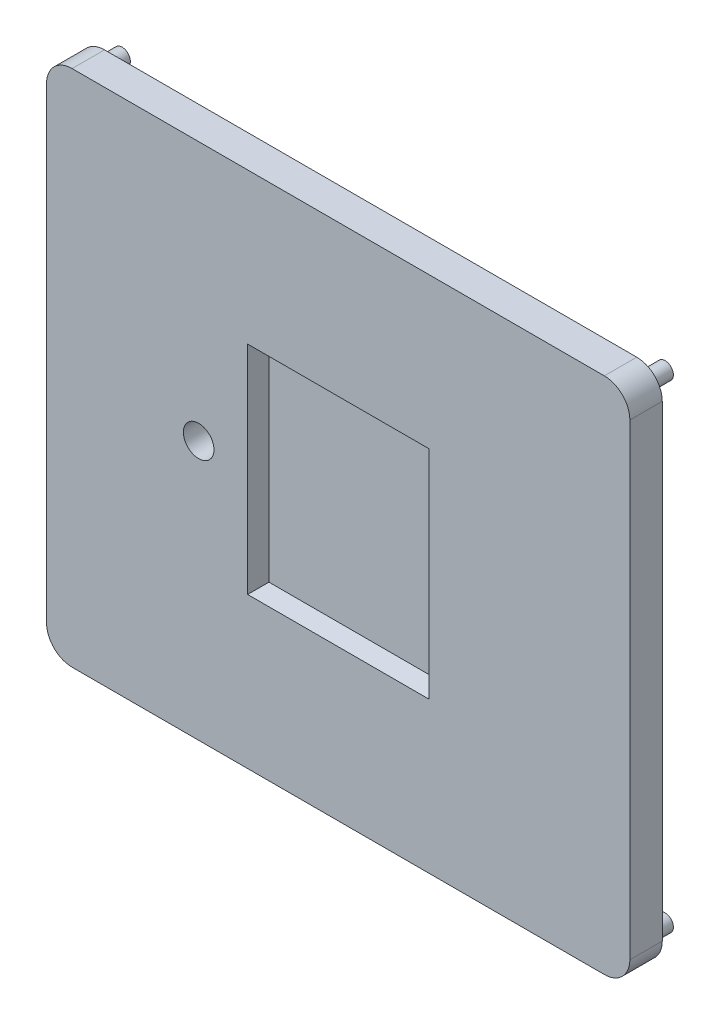
SolidWorks part; units mm, degrees
material "ABS"
ref_plane "Front Plane" through (0, 0, 0) normal (0, 0, 1) x (1, 0, 0)
ref_plane "Top Plane" through (0, 0, 0) normal (0, 1, 0) x (1, 0, 0)
ref_plane "Right Plane" through (0, 0, 0) normal (1, 0, 0) x (0, 0, -1)
sketch "Sketch1" plane through (-2.5661, -10, 0) normal (0, 0, 1) x (1, 0, 0)
  line L1 (-145.6036, 92.4468) -> (62.9964, 92.4468)
  line L2 (-155.6036, 82.4468) -> (-155.6036, -100.7532)
  line L3 (-145.6036, -110.7532) -> (62.9964, -110.7532)
  line L4 (72.9964, 82.4468) -> (72.9964, -100.7532)
  arc A0 (-145.6036, 92.4468) -> (-155.6036, 82.4468) centre (-145.6036, 82.4468) ccw
  arc A1 (-155.6036, -100.7532) -> (-145.6036, -110.7532) centre (-145.6036, -100.7532) ccw
  arc A2 (62.9964, -110.7532) -> (72.9964, -100.7532) centre (62.9964, -100.7532) ccw
  arc A3 (62.9964, 92.4468) -> (72.9964, 82.4468) centre (62.9964, 82.4468) cw
  point P6 (-155.6036, 92.4468)
  point P9 (-155.6036, -110.7532)
  point P14 (72.9964, 92.4468)
  dimension "D3" = 10
  dimension "D4" = 10
  dimension "D5" = 10
  dimension "D6" = 10
  dimension "D1" = 203.2
  dimension "D2" = 228.6
extrude "Lid" add sketch "Sketch1" along normal blind 12.7
sketch "Sketch2" plane through (0, 0, 0) normal (0, 0, 1) x (1, 0, 0)
  line L0 (67.5014, 79.5179) -> (64.8497, 76.8663)
  line L1 (67.5014, -117.8242) -> (64.8497, -115.1726)
  line L2 (-155.2408, 79.5179) -> (-152.5891, 76.8663)
  line L3 (-155.2408, -117.8242) -> (-152.5891, -115.1726)
  line L4 (60.2535, 72.2701) -> (57.7303, 69.7468)
  line L5 (60.2535, -110.5764) -> (68.9341, -119.2569)
  line L6 (-147.9929, -110.5764) -> (-131.8167, -94.4002)
  line L7 (-147.9929, 72.2701) -> (-143.1975, 67.4746)
  line L8 (70.4303, -110.7532) -> (70.4303, 72.4468) construction
  line L9 (57.7303, -108.0532) -> (-145.4697, -108.0532)
  line L10 (57.7303, -108.0532) -> (57.7303, 69.7468)
  line L11 (57.7303, 69.7468) -> (-145.4697, 69.7468)
  line L12 (-145.4697, -108.0532) -> (-145.4697, 69.7468)
  line L13 (-158.1697, 72.4468) -> (-158.1697, -110.7532) construction
  line L14 (60.4303, 82.4468) -> (-148.1697, 82.4468) construction
  arc A0 (70.4303, 72.4468) -> (60.4303, 82.4468) centre (60.4303, 72.4468) ccw construction
  arc A1 (60.4303, -120.7532) -> (70.4303, -110.7532) centre (60.4303, -110.7532) ccw construction
  arc A2 (-148.1697, 82.4468) -> (-158.1697, 72.4468) centre (-148.1697, 72.4468) ccw construction
  arc A3 (-158.1697, -110.7532) -> (-148.1697, -120.7532) centre (-148.1697, -110.7532) ccw construction
  circle A4 centre (62.5516, 74.5682) radius 3.25
  circle A5 centre (62.5516, -112.8745) radius 3.25
  circle A6 centre (-150.291, -112.8745) radius 3.25
  circle A7 centre (-150.291, 74.5682) radius 3.25
  circle A8 centre (62.5516, -112.8745) radius 3.5
  dimension "D1" = 6.5
  dimension "D9" = 7
  dimension "D2" = 7
  dimension "D3" = 7
  dimension "D4" = 7
  dimension "D5" = 7
  dimension "D6" = 12.7
  dimension "D7" = 12.7
  dimension "D8" = 12.7
extrude "Corner Shafts" add sketch "Sketch2" against normal blind 9 contours A4 | A5 | A6 | A7
ref_plane "Top - Outer Plane" through (0, 0, 12.7) normal (0, 0, 1) x (1, 0, 0)
ref_plane "Plane - Top for Kinect" through (0, 0, 12.7) normal (0, 0, 1) x (1, 0, 0)
sketch "Center Lines" plane through (0, 0, 12.7) normal (0, 0, 1) x (1, 0, 0)
  line L0 (70.4303, -19.1532) -> (-185.234, -19.1532) construction
  line L1 (70.4303, -110.7532) -> (70.4303, 72.4468) construction
  line L2 (-43.8697, 82.4468) -> (-43.8697, -133.2416) construction
  line L3 (60.4303, 82.4468) -> (-148.1697, 82.4468) construction
ref_plane "Plane - Base for Kinect" through (0, 0, 6.35) normal (0, 0, 1) x (1, 0, 0)
sketch "Base for Kinect" plane through (0, 0, 6.35) normal (0, 0, 1) x (1, 0, 0)
  line L0 (-43.8697, 82.4468) -> (-43.8697, -133.2416) construction
  line L1 (-10.3697, 21.3468) -> (-77.3697, 21.3468)
  line L2 (-10.3697, 21.3468) -> (-10.3697, -59.6532)
  line L3 (-10.3697, -59.6532) -> (-77.3697, -59.6532)
  line L4 (-77.3697, 21.3468) -> (-77.3697, -59.6532)
  line L5 (70.4303, -19.1532) -> (-185.234, -19.1532) construction
  dimension "D1" = 67
  dimension "D2" = 81
  dimension "D3" = 33.5
  dimension "D4" = 40.5
sketch "Sketch8" plane through (0, 0, 12.7) normal (0, 0, 1) x (1, 0, 0)
  line L0 (70.4303, -19.1532) -> (-185.234, -19.1532) construction
  line L1 (-8.3697, 23.3468) -> (-79.3697, 23.3468)
  line L2 (-8.3697, 23.3468) -> (-8.3697, -61.6532)
  line L3 (-8.3697, -61.6532) -> (-79.3697, -61.6532)
  line L4 (-79.3697, 23.3468) -> (-79.3697, -61.6532)
  line L5 (-43.8697, 82.4468) -> (-43.8697, -133.2416) construction
  dimension "D1" = 71
  dimension "D2" = 85
  dimension "D3" = 42.5
  dimension "D4" = 35.5
loft "Kinect Loft Cut" cut profiles "Sketch8", "Base for Kinect"
sketch "Sketch9" plane through (0, 0, 12.7) normal (0, 0, 1) x (1, 0, 0)
  line L0 (70.4303, -19.1532) -> (-185.234, -19.1532) construction
  circle A0 centre (-98.5666, -19.1532) radius 6
  point P4 (-98.5666, -19.1532)
  dimension "D1" = 12
extrude "Wire Hole" cut sketch "Sketch9" against normal through all
